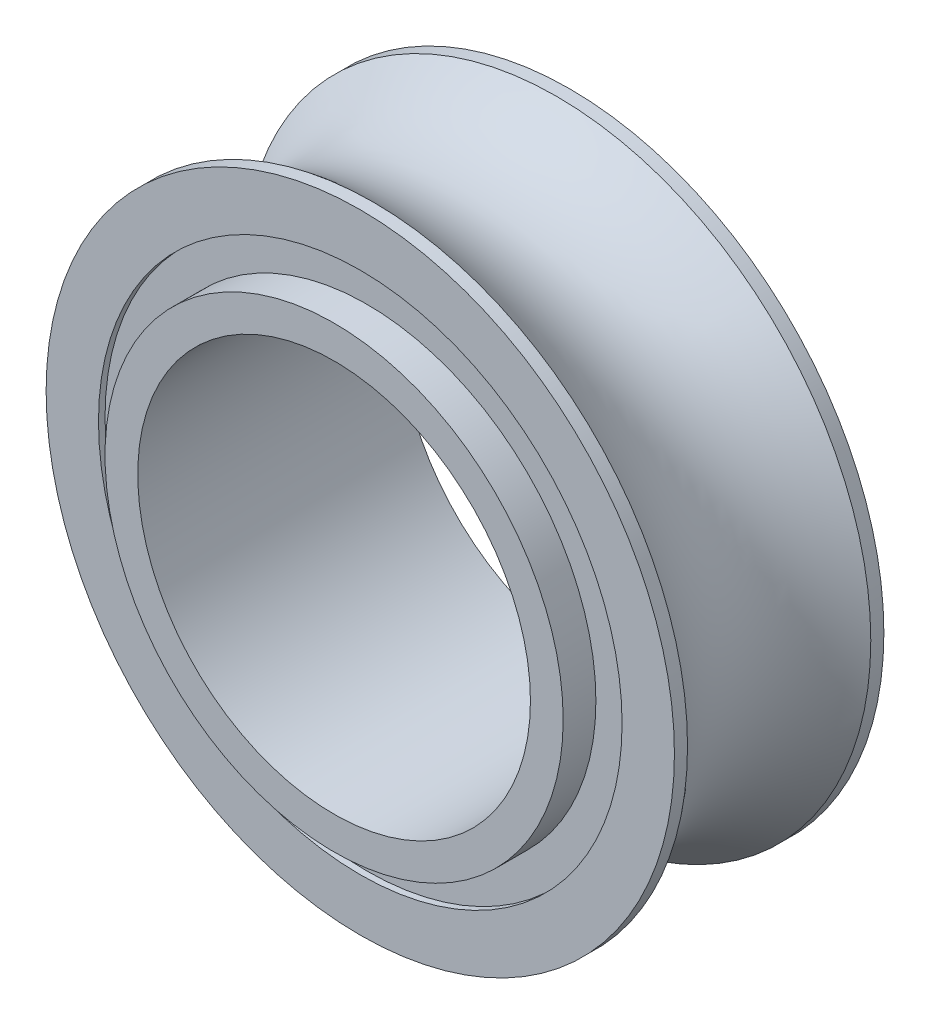
SolidWorks part; units mm, degrees
ref_plane "Front Plane" through (0, 0, 0) normal (0, 0, 1) x (1, 0, 0)
ref_plane "Top Plane" through (0, 0, 0) normal (0, 1, 0) x (1, 0, 0)
ref_plane "Right Plane" through (0, 0, 0) normal (1, 0, 0) x (0, 0, -1)
sketch "Sketch1" plane through (0, 0, 0) normal (0, 0, 1) x (1, 0, 0)
  circle A0 centre (0, 0) radius 19.05
  circle A1 centre (0, 0) radius 22.225
  dimension "D1" = 38.1
  dimension "D2" = 44.45
extrude "Boss-Extrude1" add sketch "Sketch1" along normal mid plane 25.4
sketch "Sketch2" plane through (0, 0, 0) normal (0, 0, 1) x (1, 0, 0)
  circle A0 centre (0, 0) radius 22.225
  circle A1 centre (0, 0) radius 25.4
  dimension "D1" = 44.45
  dimension "D2" = 50.8
extrude "Boss-Extrude2" add sketch "Sketch2" along normal mid plane 19.05
sketch "Sketch3" plane through (0, 0, 0) normal (0, 0, 1) x (1, 0, 0)
  circle A0 centre (0, 0) radius 25.4
  circle A1 centre (0, 0) radius 30.48
  dimension "D1" = 50.8
  dimension "D2" = 60.96
extrude "Boss-Extrude3" add sketch "Sketch3" along normal mid plane 20.32
sketch "Sketch4" plane through (0, 0, 0) normal (1, 0, 0) x (0, 0, -1)
  line L0 (0, 32.1192) -> (0, 30.48) construction
  line L2 (10.16, 30.48) -> (-10.16, 30.48) construction
  line L4 (0, 26.67) -> (0, -38.2325) construction
  line L5 (-8.89, 30.48) -> (8.89, 30.48)
  line L6 (0, 0) -> (16.7974, 0) construction
  spline S0 degree 2 poles (-8.89, 30.48) (0, 22.86) (8.89, 30.48) knots 0 0 0 1 1 1
  dimension "D1" = 8.89
  dimension "D2" = 17.78
  dimension "D3" = 3.81
revolve "Cut-Revolve2" cut sketch "Sketch4" angle 360 about L6
